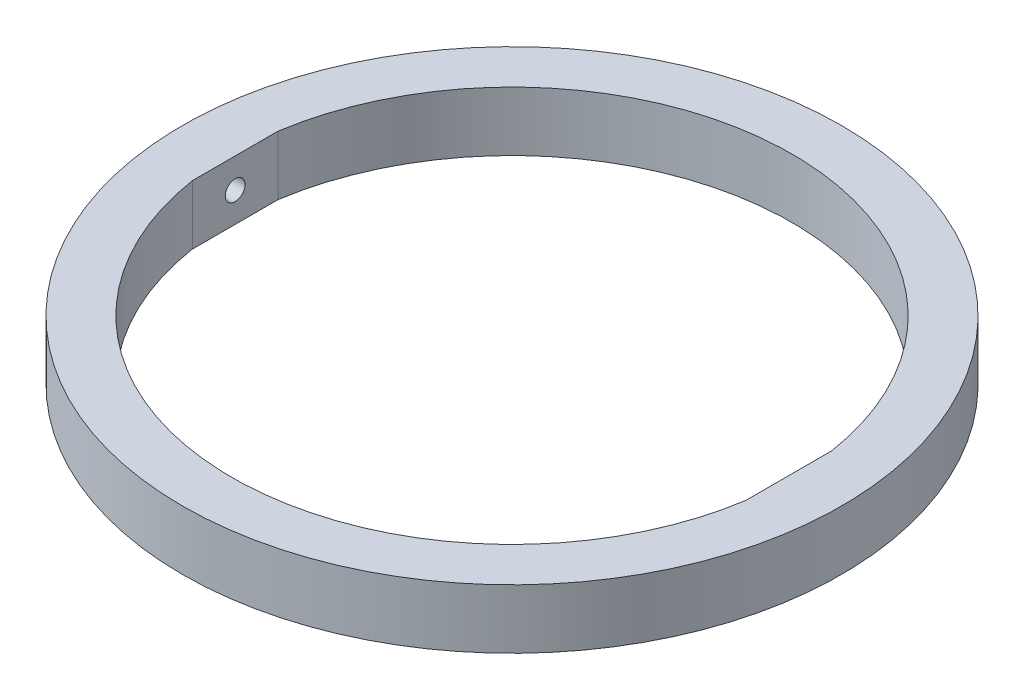
SolidWorks part; units mm, degrees
ref_plane "Front Plane" through (0, 0, 0) normal (0, 0, 1) x (1, 0, 0)
ref_plane "Top Plane" through (0, 0, 0) normal (0, 1, 0) x (1, 0, 0)
ref_plane "Right Plane" through (0, 0, 0) normal (1, 0, 0) x (0, 0, -1)
sketch "Sketch1" plane through (0, 0, 0) normal (0, 1, 0) x (1, 0, 0)
  circle A0 centre (0, 0) radius 42.5
  circle A1 centre (0, 0) radius 50
  dimension "D1" = 85
  dimension "D2" = 100
extrude "Boss-Extrude1" add sketch "Sketch1" along normal blind 9
sketch "Sketch2" plane through (0, 9, 0) normal (0, 1, 0) x (1, 0, 0)
  line L1 (42, -6.5) -> (-42, -6.5)
  line L2 (42, -6.5) -> (42, 6.5)
  line L3 (42, 6.5) -> (-42, 6.5)
  line L4 (-42, -6.5) -> (-42, 6.5)
  line L5 (42, -6.5) -> (-42, 6.5) construction
  line L6 (42, 6.5) -> (-42, -6.5) construction
  circle A0 centre (0, 0) radius 42.5
  circle A1 centre (0, 0) radius 42.5 construction
  circle M6 centre (0, 0) radius 42.5
  dimension "D2" = 0
  dimension "D1" = 84
extrude "Boss-Extrude2" add sketch "Sketch2" against normal blind 9 contours L4 M6 | L2 M6
sketch "Sketch3" plane through (-42, 0, 0) normal (1, 0, 0) x (0, 0, -1)
  line L0 (-6.5, 0) -> (6.5, 0) construction
  circle A0 centre (0, 4.5) radius 1.5
  dimension "D1" = 3
  dimension "D2" = 4.5
extrude "Cut-Extrude1" cut sketch "Sketch3" against normal blind 5 and the other way blind 89
